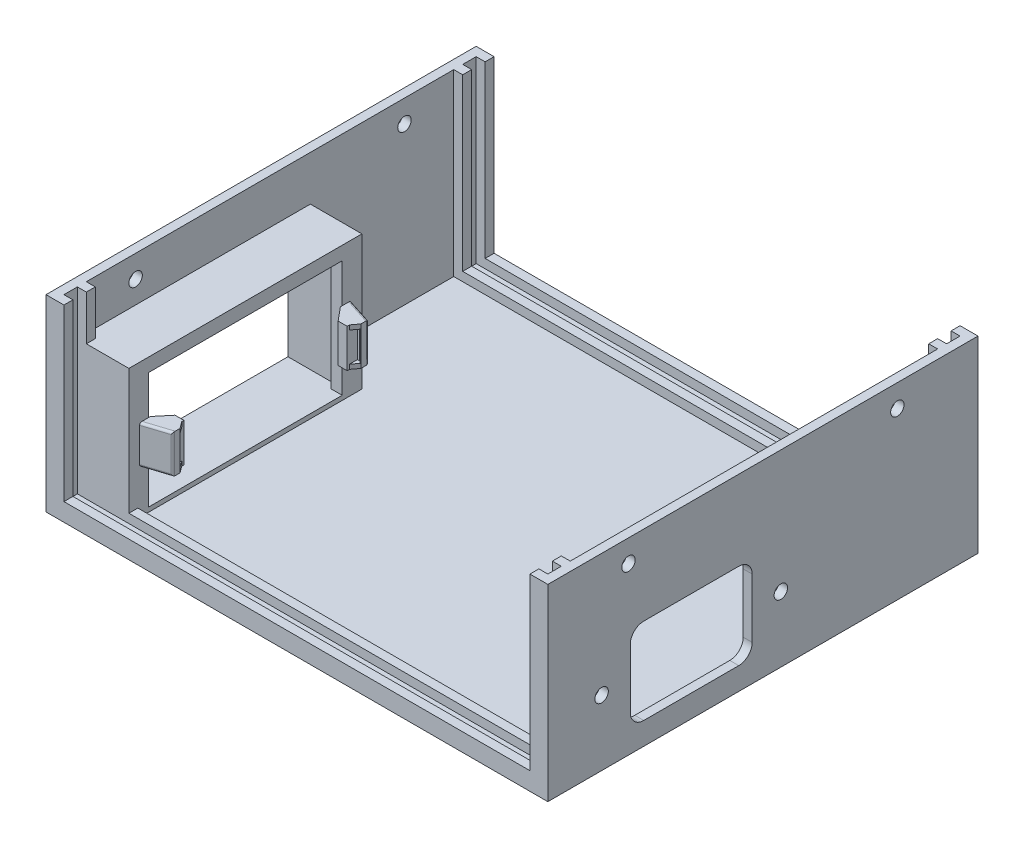
SolidWorks part; units mm, degrees
ref_plane "Plano frontal" through (0, 0, 0) normal (0, 0, 1) x (1, 0, 0)
ref_plane "Plano superior" through (0, 0, 0) normal (0, 1, 0) x (1, 0, 0)
ref_plane "Plano direito" through (0, 0, 0) normal (1, 0, 0) x (0, 0, -1)
sketch "Esboço1" plane through (0, 0, 0) normal (0, 1, 0) x (1, 0, 0)
  line L1 (0, 0) -> (112, 0)
  line L2 (0, 0) -> (0, 96)
  line L3 (0, 96) -> (112, 96)
  line L4 (112, 0) -> (112, 96)
  dimension "D1" = 96
  dimension "D2" = 112
extrude "Ressalto-extrusão1" add sketch "Esboço1" along normal blind 2
sketch "Esboço2" plane through (0, 2, 0) normal (0, 1, 0) x (1, 0, 0)
  line L0 (0, 0) -> (112, 0) construction
  line L1 (0, 96) -> (2, 96)
  line L2 (0, 96) -> (0, 0)
  line L3 (0, 0) -> (2, 0)
  line L4 (2, 94) -> (2, 91)
  line L5 (2, 5) -> (2, 2)
  line L6 (112, 96) -> (110, 96)
  line L7 (112, 96) -> (112, 0)
  line L8 (112, 0) -> (110, 0)
  line L9 (110, 94) -> (110, 91)
  line L10 (2, 96) -> (110, 96)
  line L12 (2, 94) -> (110, 94)
  line L14 (2, 91) -> (110, 91)
  line L16 (2, 89) -> (110, 89)
  line L18 (2, 0) -> (110, 0)
  line L20 (2, 2) -> (110, 2)
  line L22 (110, 5) -> (2, 5)
  line L24 (110, 7) -> (2, 7)
  line L26 (110, 5) -> (110, 2)
  line L27 (110, 89) -> (110, 7)
  line L28 (2, 89) -> (2, 7)
  dimension "D1" = 2
  dimension "D2" = 2
  dimension "D3" = 2
  dimension "D4" = 3
  dimension "D5" = 2
  dimension "D6" = 2
  dimension "D7" = 3
  dimension "D8" = 2
extrude "Ressalto-extrusão2" add sketch "Esboço2" along normal blind 40
sketch "Esboço3" plane through (0, 0, 0) normal (0, 0, 1) x (1, 0, 0)
  line L0 (0, 42) -> (112, 42) construction
  line L1 (4, 42) -> (108, 42)
  line L2 (4, 42) -> (4, 4)
  line L3 (4, 4) -> (108, 4)
  line L4 (108, 42) -> (108, 4)
  line L5 (0, 0) -> (112, 0) construction
  line L6 (0, 42) -> (0, 0) construction
  line L7 (112, 42) -> (112, 0) construction
  dimension "D1" = 4
  dimension "D2" = 4
  dimension "D3" = 4
extrude "Corte-extrusão1" cut sketch "Esboço3" against normal through all
sketch "Esboço4" plane through (2, 0, 0) normal (1, 0, 0) x (0, 0, -1)
  line L1 (57, 32) -> (5, 32)
  line L2 (57, 32) -> (57, 2)
  line L3 (57, 2) -> (5, 2)
  line L4 (5, 32) -> (5, 2)
  dimension "D1" = 52
  dimension "D2" = 30
extrude "Ressalto-extrusão3" add sketch "Esboço4" along normal blind 11.5
sketch "Esboço5" plane through (0, 0, 0) normal (-1, 0, 0) x (0, 0, 1)
  line L0 (-96, 0) -> (0, 0) construction
  line L1 (-8, 3) -> (-54, 3)
  line L2 (-8, 3) -> (-8, 29)
  line L3 (-8, 29) -> (-54, 29)
  line L4 (-54, 3) -> (-54, 29)
  line L5 (0, 42) -> (0, 0) construction
  dimension "D1" = 46
  dimension "D2" = 26
  dimension "D3" = 3
  dimension "D4" = 8
extrude "Corte-extrusão2" cut sketch "Esboço5" against normal blind 12
sketch "Esboço6" plane through (12, 0, 0) normal (-1, 0, 0) x (0, 0, 1)
  line L0 (-8, 29) -> (-54, 29) construction
  line L1 (-52.6, 29) -> (-9.4, 29)
  line L2 (-52.6, 29) -> (-52.6, 3)
  line L3 (-52.6, 3) -> (-9.4, 3)
  line L4 (-9.4, 29) -> (-9.4, 3)
  line L5 (-54, 3) -> (-8, 3) construction
  line L6 (-54, 29) -> (-54, 3) construction
  dimension "D1" = 43.2
  dimension "D2" = 1.4
extrude "Corte-extrusão3" cut sketch "Esboço6" against normal blind 1.5
sketch "Esboço7" plane through (0, 3, 0) normal (0, 1, 0) x (1, 0, 0)
  line L0 (12, 52.6) -> (12, 53.6)
  line L1 (12, 52.6) -> (12, 54) construction
  line L2 (12, 53.6) -> (11, 52.6)
  line L3 (11, 52.6) -> (12, 52.6)
  line L4 (12, 9.4) -> (12, 8.4)
  line L5 (12, 8) -> (12, 9.4) construction
  line L6 (12, 8.4) -> (11, 9.4)
  line L7 (11, 9.4) -> (12, 9.4)
  dimension "D1" = 1
  dimension "D2" = 1
  dimension "D3" = 1
  dimension "D4" = 1
extrude "Ressalto-extrusão4" add sketch "Esboço7" along normal blind 26
sketch "Esboço8" plane through (13.5, 0, 0) normal (1, 0, 0) x (0, 0, -1)
  line L0 (57, 32) -> (5, 32) construction
  line L1 (7.4, 20.3) -> (12.8, 20.3)
  line L2 (7.4, 20.3) -> (7.4, 11.7)
  line L3 (7.4, 11.7) -> (12.8, 11.7)
  line L4 (12.8, 20.3) -> (12.8, 11.7)
  line L5 (54.6, 20.3) -> (49.2, 20.3)
  line L6 (54.6, 20.3) -> (54.6, 11.7)
  line L7 (54.6, 11.7) -> (49.2, 11.7)
  line L8 (49.2, 20.3) -> (49.2, 11.7)
  line L9 (57, 32) -> (7, 32) construction
  line L10 (9.4, 3) -> (9.4, 29) construction
  line L11 (52.6, 29) -> (52.6, 3) construction
  dimension "D1" = 8.6
  dimension "D2" = 8.6
  dimension "D3" = 11.7
  dimension "D4" = 11.7
  dimension "D5" = 5.4
  dimension "D6" = 5.4
  dimension "D7" = 2
  dimension "D8" = 2
extrude "Ressalto-extrusão5" add sketch "Esboço8" along normal blind 5.6
sketch "Esboço9" plane through (0, 20.3, 0) normal (0, 1, 0) x (1, 0, 0)
  line L0 (13.5, 54.6) -> (19.1, 52.8)
  line L1 (19.1, 54.6) -> (19.1, 49.2) construction
  line L2 (19.1, 52.8) -> (19.1, 54.6)
  line L3 (19.1, 54.6) -> (13.5, 54.6) construction
  line L4 (19.1, 54.6) -> (13.5, 54.6)
  line L5 (13.5, 7.4) -> (19.1, 7.4)
  line L6 (19.1, 7.4) -> (19.1, 9.2)
  line L7 (19.1, 12.8) -> (19.1, 7.4) construction
  line L8 (19.1, 9.2) -> (13.5, 7.4)
  dimension "D1" = 1.8
  dimension "D2" = 1.8
extrude "Corte-extrusão4" cut sketch "Esboço9" against normal blind 8.6
sketch "Esboço10" plane through (0, 20.3, 0) normal (0, 1, 0) x (1, 0, 0)
  line L0 (13.5, 12.8) -> (16, 12.8)
  line L1 (19.1, 12.8) -> (13.5, 12.8) construction
  line L2 (16, 12.8) -> (13.5, 9.8)
  line L3 (13.5, 57) -> (13.5, 5) construction
  line L4 (13.5, 9.8) -> (13.5, 12.8)
  line L5 (13.5, 49.2) -> (16, 49.2)
  line L6 (19.1, 49.2) -> (13.5, 49.2) construction
  line L7 (16, 49.2) -> (13.5, 52.2)
  line L8 (13.5, 52.6) -> (13.5, 49.2) construction
  line L9 (13.5, 52.2) -> (13.5, 49.2)
  dimension "D1" = 2.5
  dimension "D2" = 3
  dimension "D3" = 2.5
  dimension "D4" = 3
extrude "Corte-extrusão5" cut sketch "Esboço10" against normal blind 8.6
sketch "Esboço11" plane through (0, 20.3, 0) normal (0, 1, 0) x (1, 0, 0)
  line L0 (19.1, 49.2) -> (18, 49.2)
  line L1 (18, 49.2) -> (18, 49.7)
  line L2 (18, 49.7) -> (19.1, 51.2)
  line L3 (19.1, 52.8) -> (19.1, 49.2) construction
  line L4 (19.1, 51.2) -> (19.1, 49.2)
  line L5 (13.5, 7) -> (13.5, 57) construction
  line L6 (19.1, 12.8) -> (18, 12.8)
  line L7 (19.1, 12.8) -> (16, 12.8) construction
  line L8 (18, 12.8) -> (18, 12.3)
  line L9 (18, 12.3) -> (19.1, 10.8)
  line L10 (19.1, 12.8) -> (19.1, 9.2) construction
  line L11 (19.1, 10.8) -> (19.1, 12.8)
  line L12 (13.5, 57) -> (13.5, 5) construction
  dimension "D1" = 2
  dimension "D2" = 4.5
  dimension "D3" = 0.5
  dimension "D4" = 2
  dimension "D5" = 4.5
  dimension "D6" = 0.5
extrude "Corte-extrusão6" cut sketch "Esboço11" against normal blind 8.6
ref_plane "Plano1" through (0, 19.3, 0) normal (0, 1, 0) x (1, 0, 0)
sketch "Esboço14" plane through (0, 19.3, 0) normal (0, 1, 0) x (1, 0, 0)
  line L0 (18, 12.3) -> (18, 10.5)
  line L1 (18, 10.5) -> (18.5, 10.5)
  line L2 (18.5, 10.5) -> (19.0332, 10.891)
  line L3 (18, 12.3) -> (19.1, 10.8) construction
  line L4 (18, 49.7) -> (18, 51.5)
  line L5 (18, 51.5) -> (18.5, 51.5)
  line L6 (18.5, 51.5) -> (19.0332, 51.109)
  line L7 (19.1, 51.2) -> (18, 49.7) construction
  line L8 (18, 49.7) -> (19.0332, 51.109)
  line L9 (18, 12.3) -> (19.0332, 10.891)
  dimension "D1" = 1.8
  dimension "D2" = 0.5
  dimension "D3" = 90
  dimension "D4" = 1.8
  dimension "D5" = 0.5
  dimension "D6" = 90
extrude "Corte-extrusão7" cut sketch "Esboço14" against normal blind 6.6
fillet "Filete1" radius 0.5 3 edges at (19.1, 16, -52.8) (16.3, 11.7, -53.7) (16.3, 20.3, -53.7)
fillet "Filete2" radius 0.5 3 edges at (19.1, 16, -9.2) (16.3, 11.7, -8.3) (16.3, 20.3, -8.3)
sketch "Esboço15" plane through (112, 0, 0) normal (1, 0, 0) x (0, 0, -1)
  line L0 (0, 42) -> (0, 0) construction
  line L1 (21.4, 5) -> (42.6, 5)
  line L2 (18.4, 8) -> (18.4, 21.2)
  line L3 (21.4, 24.2) -> (42.6, 24.2)
  line L4 (45.6, 8) -> (45.6, 21.2)
  line L5 (0, 0) -> (96, 0) construction
  arc A0 (18.4, 8) -> (21.4, 5) centre (21.4, 8) ccw
  arc A1 (42.6, 5) -> (45.6, 8) centre (42.6, 8) ccw
  arc A2 (42.6, 24.2) -> (45.6, 21.2) centre (42.6, 21.2) cw
  arc A3 (18.4, 21.2) -> (21.4, 24.2) centre (21.4, 21.2) cw
  point P12 (45.6, 5)
  point P15 (45.6, 24.2)
  point P18 (18.4, 24.2)
  dimension "D5" = 3
  dimension "D1" = 27.2
  dimension "D2" = 19.2
  dimension "D3" = 18.4
  dimension "D4" = 5
extrude "Corte-extrusão8" cut sketch "Esboço15" against normal blind 2
sketch "Esboço16" plane through (112, 0, 0) normal (1, 0, 0) x (0, 0, -1)
  line L0 (5.8277, 14.6) -> (60.3243, 14.6) construction
  line L1 (18.4, 21.2) -> (18.4, 8) construction
  circle A0 centre (52, 14.6) radius 1.5
  circle A1 centre (12, 14.6) radius 1.5
  dimension "D3" = 3
  dimension "D4" = 3
  dimension "D1" = 40
  dimension "D2" = 6.4
extrude "Corte-extrusão9" cut sketch "Esboço16" against normal blind 2
sketch "Esboço17" plane through (0, 0, 0) normal (-1, 0, 0) x (0, 0, 1)
  line L0 (-96, 37) -> (0, 37) construction
  line L1 (-96, 42) -> (-96, 0) construction
  line L2 (0, 42) -> (0, 0) construction
  line L3 (-96, 42) -> (0, 42) construction
  circle A0 centre (-78, 37) radius 1.5
  circle A1 centre (-18, 37) radius 1.5
  dimension "D4" = 3
  dimension "D5" = 3
  dimension "D1" = 5
  dimension "D2" = 60
  dimension "D3" = 18
extrude "Corte-extrusão10" cut sketch "Esboço17" against normal through all
